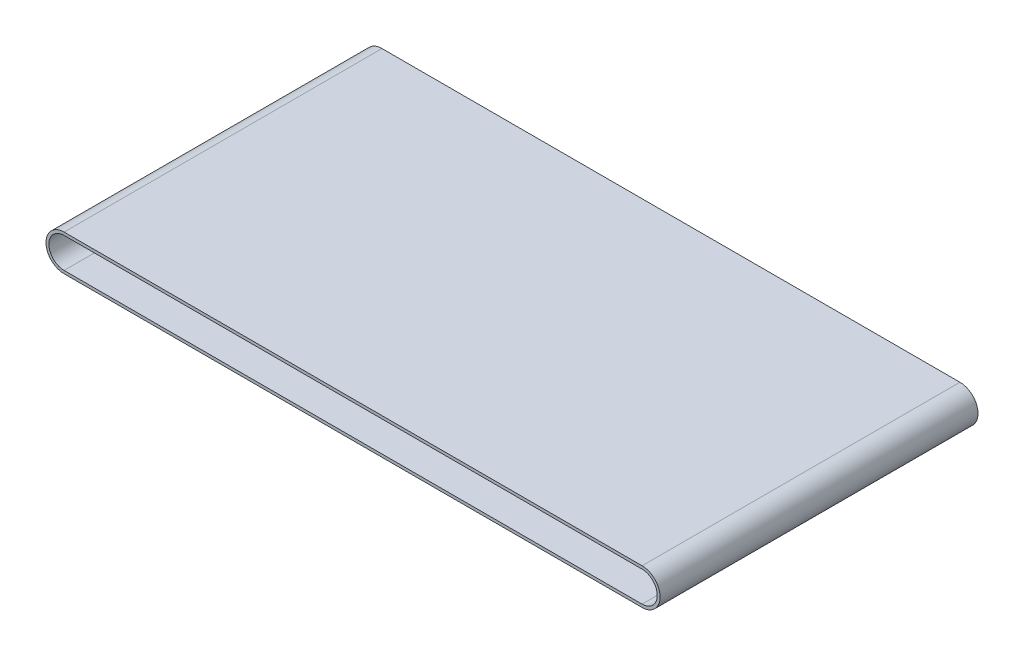
SolidWorks part; units mm, degrees
material "Malleable Cast Iron"
ref_plane "Plan de face" through (0, 0, 0) normal (0, 0, 1) x (1, 0, 0)
ref_plane "Plan de dessus" through (0, 0, 0) normal (0, 1, 0) x (1, 0, 0)
ref_plane "Plan de droite" through (0, 0, 0) normal (1, 0, 0) x (0, 0, -1)
sketch "Esquisse1" plane through (0, 0, 0) normal (0, 0, 1) x (1, 0, 0)
  line L1 (-254, 15.875) -> (254, 15.875)
  line L3 (-254, -15.875) -> (254, -15.875)
  arc A0 (-254, -15.875) -> (-254, 15.875) centre (-254, 0) cw
  arc A1 (254, 15.875) -> (254, -15.875) centre (254, 0) cw
  point P6 (-269.875, 0)
  point P7 (269.875, 0)
  point P9 (0, 15.875)
  dimension "D1" = 31.75
  dimension "D2" = 539.75
extrude "Boss.-Extru.1" add sketch "Esquisse1" along normal mid plane 279.4
sketch "Esquisse2" plane through (0, 0, 139.7) normal (0, 0, 1) x (1, 0, 0)
  line L0 (254, 15.875) -> (-254, 15.875) construction
  line L1 (-254, 13.335) -> (254, 13.335)
  line L3 (-254, -13.335) -> (254, -13.335)
  line L5 (-254, -15.875) -> (254, -15.875) construction
  arc A0 (-254, 13.335) -> (-254, -13.335) centre (-254, 0) ccw
  arc A1 (254, 13.335) -> (254, -13.335) centre (254, 0) cw
  dimension "D1" = 2.54
  dimension "D2" = 2.54
  dimension "D3" = 26.67
extrude "Enlèv. mat.-Extru.1" cut sketch "Esquisse2" against normal up to next
